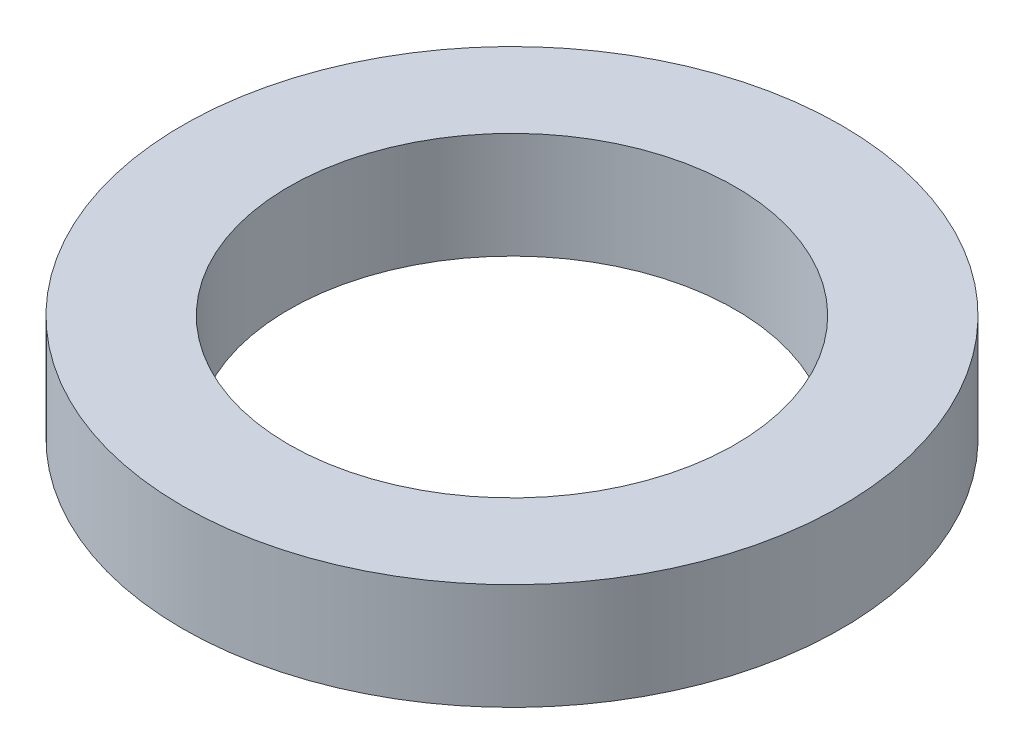
SolidWorks part; units mm, degrees
ref_plane "Front Plane" through (0, 0, 0) normal (0, 0, 1) x (1, 0, 0)
ref_plane "Top Plane" through (0, 0, 0) normal (0, 1, 0) x (1, 0, 0)
ref_plane "Right Plane" through (0, 0, 0) normal (1, 0, 0) x (0, 0, -1)
sketch "Sketch1" plane through (0, 0, 0) normal (0, 1, 0) x (1, 0, 0)
  circle A0 centre (0, 0) radius 3.1
  circle A1 centre (0, 0) radius 2.1
  dimension "D1" = 6.2
  dimension "D2" = 4.2
extrude "Boss-Extrude1" add sketch "Sketch1" along normal blind 1
